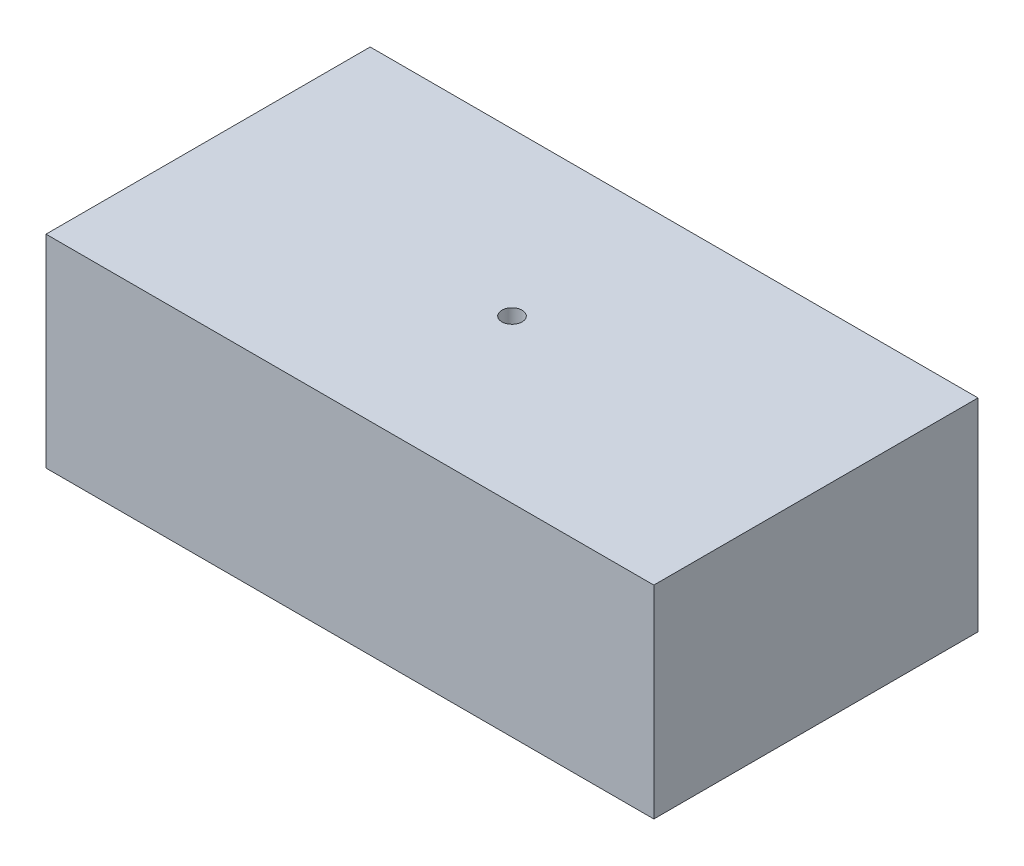
SolidWorks part; units mm, degrees
ref_plane "Front Plane" through (0, 0, 0) normal (0, 0, 1) x (1, 0, 0)
ref_plane "Top Plane" through (0, 0, 0) normal (0, 1, 0) x (1, 0, 0)
ref_plane "Right Plane" through (0, 0, 0) normal (1, 0, 0) x (0, 0, -1)
sketch "Sketch1" plane through (0, 0, 0) normal (0, 1, 0) x (1, 0, 0)
  line L1 (75, -40) -> (-75, -40)
  line L2 (75, -40) -> (75, 40)
  line L3 (75, 40) -> (-75, 40)
  line L4 (-75, -40) -> (-75, 40)
  line L5 (75, -40) -> (-75, 40) construction
  line L6 (75, 40) -> (-75, -40) construction
  point P0 (0, 0)
  dimension "D1" = 150
  dimension "D2" = 80
sketch "Sketch2" plane through (0, 0, 0) normal (0, 1, 0) x (1, 0, 0)
  line L1 (72.5, -37.5) -> (-72.5, -37.5)
  line L2 (72.5, -37.5) -> (72.5, 37.5)
  line L3 (72.5, 37.5) -> (-72.5, 37.5)
  line L4 (-72.5, -37.5) -> (-72.5, 37.5)
  line L5 (72.5, -37.5) -> (-72.5, 37.5) construction
  line L6 (72.5, 37.5) -> (-72.5, -37.5) construction
  point P0 (0, 0)
  dimension "D1" = 145
  dimension "D2" = 75
sketch "Sketch3" plane through (0, 0, 0) normal (0, 1, 0) x (1, 0, 0)
  circle A1 centre (0, 0) radius 2.5
extrude "Boss-Extrude4" add sketch "Sketch1" along normal blind 50
extrude "Cut-Extrude12" cut sketch "Sketch2" along normal blind 45
extrude "Cut-Extrude13" cut sketch "Sketch3" along normal through all contours A1
